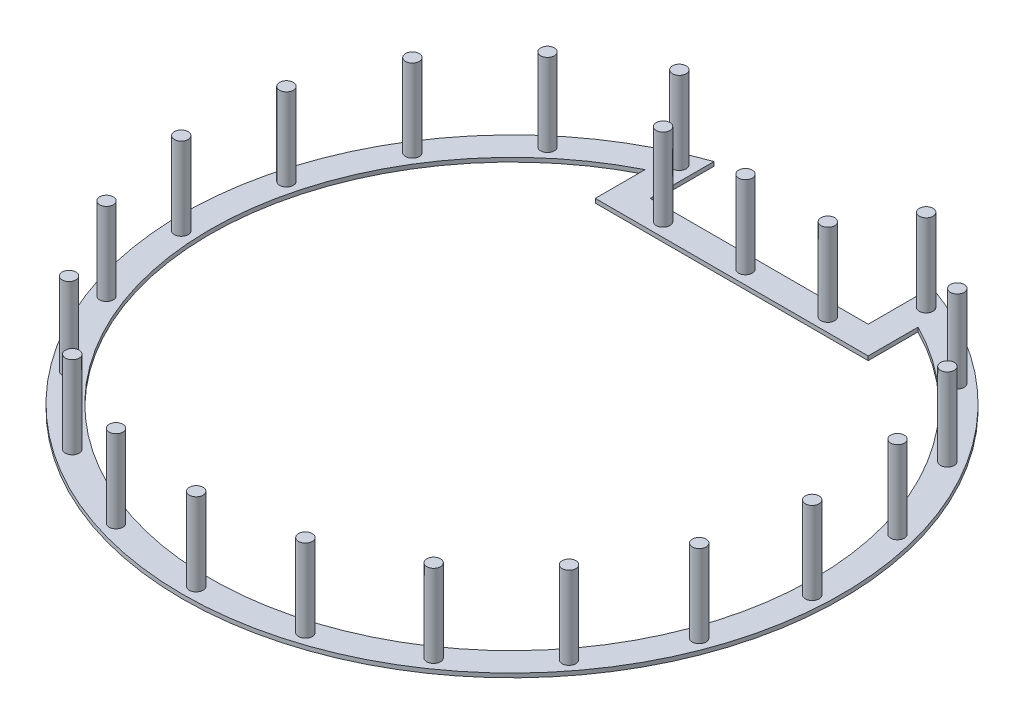
SolidWorks part; units mm, degrees
ref_plane "Front Plane" through (0, 0, 0) normal (0, 0, 1) x (1, 0, 0)
ref_plane "Top Plane" through (0, 0, 0) normal (0, 1, 0) x (1, 0, 0)
ref_plane "Right Plane" through (0, 0, 0) normal (1, 0, 0) x (0, 0, -1)
sketch "Sketch2" plane through (0, 0, 0) normal (0, 1, 0) x (1, 0, 0)
  line L0 (0, 12000) -> (0, 9000) construction
  line L1 (-7937.2539, 9000) -> (7937.2539, 9000)
  line L2 (-4218.0821, 9000) -> (-4218.0821, 11234.2238) construction
  line L3 (4218.0821, 9000) -> (4218.0821, 11234.2238) construction
  circle A0 centre (0, 0) radius 12000
  dimension "D1" = 24000
  dimension "D2" = 3000
  dimension "D3" = 7937.2539
extrude "Boss-Extrude1" add sketch "Sketch2" along normal blind 150 contours L1 A0
sketch "Sketch3" plane through (0, 150, 0) normal (0, 1, 0) x (1, 0, 0)
  line L0 (0, 9000) -> (0, 12000) construction
  line L1 (-7937.2539, 9000) -> (7937.2539, 9000) construction
  line L2 (-3968.627, 9000) -> (-7937.2539, 9000)
  line L3 (-3968.627, 9000) -> (-3968.627, 11324.7517)
  line L4 (3968.627, 9000) -> (7937.2539, 9000)
  line L5 (3968.627, 9000) -> (3968.627, 11324.7517)
  arc A0 (7937.2539, 9000) -> (-7937.2539, 9000) centre (0, 0) ccw construction
  arc A1 (-7937.2539, 9000) -> (-3968.627, 11324.7517) centre (0, 0) cw
  arc A2 (7937.2539, 9000) -> (3968.627, 11324.7517) centre (0, 0) ccw
extrude "Boss-Extrude2" add sketch "Sketch3" against normal blind 150
sketch "Sketch4" plane through (0, 150, 0) normal (0, 1, 0) x (1, 0, 0)
  line L6 (4968.627, 8000) -> (-4968.627, 8000)
  line L7 (-4968.627, 8000) -> (-4968.627, 9813.9057)
  line L8 (4968.627, 9813.9057) -> (4968.627, 8000)
  line L9 (4968.627, 8000) -> (-4968.627, 8000)
  line L10 (-4968.627, 8000) -> (-4968.627, 9813.9057)
  line L11 (4968.627, 9813.9057) -> (4968.627, 8000)
  arc A2 (-4968.627, 9813.9057) -> (4968.627, 9813.9057) centre (0, 0) ccw
  arc A3 (-4968.627, 9813.9057) -> (4968.627, 9813.9057) centre (0, 0) ccw
  dimension "D1" = 1000
extrude "Cut-Extrude1" cut sketch "Sketch4" against normal blind 2000
sketch "Sketch5" plane through (0, 150, 0) normal (0, 1, 0) x (1, 0, 0)
  line L0 (0, -12000) -> (0, -11000) construction
  arc A1 (-3968.627, 11324.7517) -> (3968.627, 11324.7517) centre (0, 0) ccw construction
  arc A2 (-4968.627, 9813.9057) -> (4968.627, 9813.9057) centre (0, 0) ccw construction
  circle A3 centre (0, -11500) radius 250
  dimension "D1" = 500
extrude "Boss-Extrude4" add sketch "Sketch5" along normal blind 3000
pattern_circular "CirPattern3" count 10 over 157 about axis through (0, 0, 0) along (0, 1, 0) of "Boss-Extrude4"
sketch "Sketch6" plane through (0, 150, 0) normal (0, 1, 0) x (1, 0, 0)
  line L0 (0, 9000) -> (0, 8000) construction
  line L1 (-3968.627, 9000) -> (3968.627, 9000) construction
  line L2 (4968.627, 8000) -> (-4968.627, 8000) construction
  circle A0 centre (0, 8500) radius 250
  dimension "D1" = 500
extrude "Boss-Extrude5" add sketch "Sketch6" along normal blind 3000
pattern_linear "LPattern1" count 2 spacing 3000 along (1, 0, 0) count 2 spacing 3000 along (-1, 0, 0) of "Boss-Extrude5"
